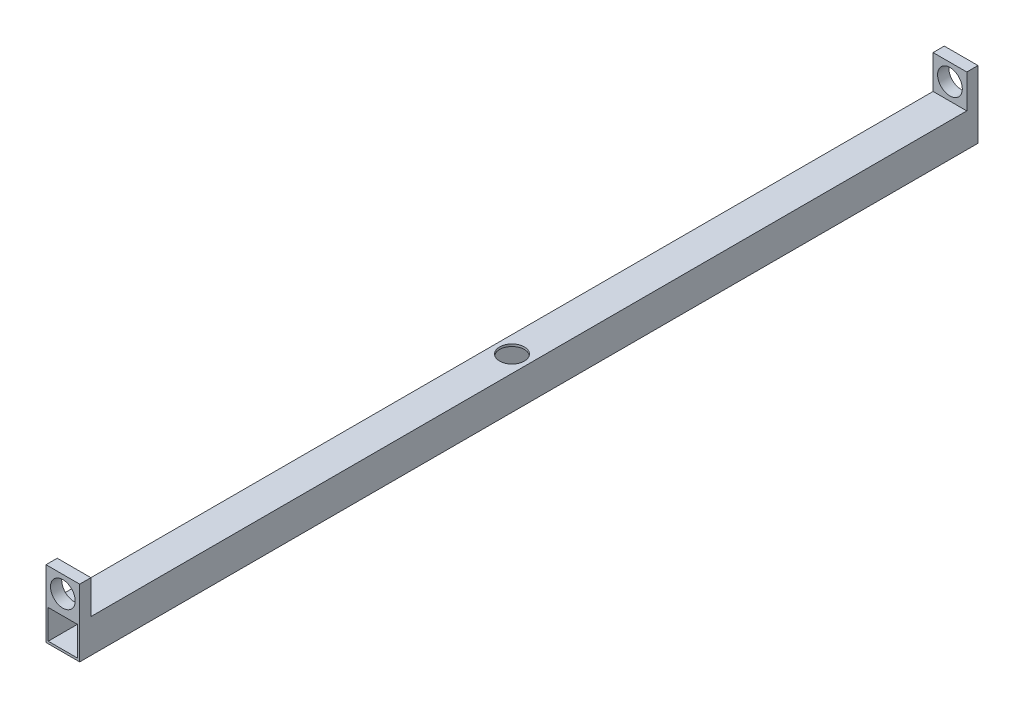
SolidWorks part; units mm, degrees
ref_plane "Front Plane" through (0, 0, 0) normal (0, 0, 1) x (1, 0, 0)
ref_plane "Top Plane" through (0, 0, 0) normal (0, 1, 0) x (1, 0, 0)
ref_plane "Right Plane" through (0, 0, 0) normal (1, 0, 0) x (0, 0, -1)
sketch "Sketch1" plane through (0, 0, 0) normal (0, 0, 1) x (1, 0, 0)
  line L1 (15, 15) -> (-15, 15)
  line L2 (15, 15) -> (15, -15)
  line L3 (15, -15) -> (-15, -15)
  line L4 (-15, 15) -> (-15, -15)
  line L5 (15, 15) -> (-15, -15) construction
  line L6 (15, -15) -> (-15, 15) construction
  line L7 (13, 13) -> (-13, 13)
  line L8 (13, 13) -> (13, -13)
  line L9 (13, -13) -> (-13, -13)
  line L10 (-13, 13) -> (-13, -13)
  line L11 (13, 13) -> (-13, -13) construction
  line L12 (13, -13) -> (-13, 13) construction
  point P0 (0, 0)
  point P6 (0, 0)
  point P13 (1.7496, -3.2765)
  dimension "D1" = 15
  dimension "D2" = 13
  dimension "D3" = 13
  dimension "D4" = 15
extrude "Boss-Extrude1" add sketch "Sketch1" along normal blind 800
sketch "Sketch2" plane through (0, 0, 0) normal (0, 0, -1) x (-1, 0, 0)
  line L1 (-15, 15) -> (15, 15)
  line L2 (-15, 15) -> (-15, 45)
  line L3 (-15, 45) -> (15, 45)
  line L4 (15, 15) -> (15, 45)
  circle A0 centre (0, 30) radius 11
  dimension "D3" = 22
  dimension "D1" = 30
  dimension "D2" = 15
  dimension "D4" = 15
  dimension "D5" = 15
extrude "Boss-Extrude2" add sketch "Sketch2" against normal blind 10
sketch "Sketch3" plane through (0, 0, 800) normal (0, 0, 1) x (1, 0, 0)
  line L1 (-15, 15) -> (15, 15)
  line L2 (-15, 15) -> (-15, 45)
  line L3 (-15, 45) -> (15, 45)
  line L4 (15, 15) -> (15, 45)
  circle A0 centre (0, 30) radius 11
  dimension "D1" = 22
extrude "Boss-Extrude3" add sketch "Sketch3" against normal blind 10
sketch "Sketch4" plane through (0, -15, 0) normal (0, -1, 0) x (1, 0, 0)
  line L0 (15, 800) -> (15, 0) construction
  circle A0 centre (0, 400) radius 11
  dimension "D1" = 22
  dimension "D2" = 15
  dimension "D3" = 400
extrude "Cut-Extrude1" cut sketch "Sketch4" against normal blind 50
